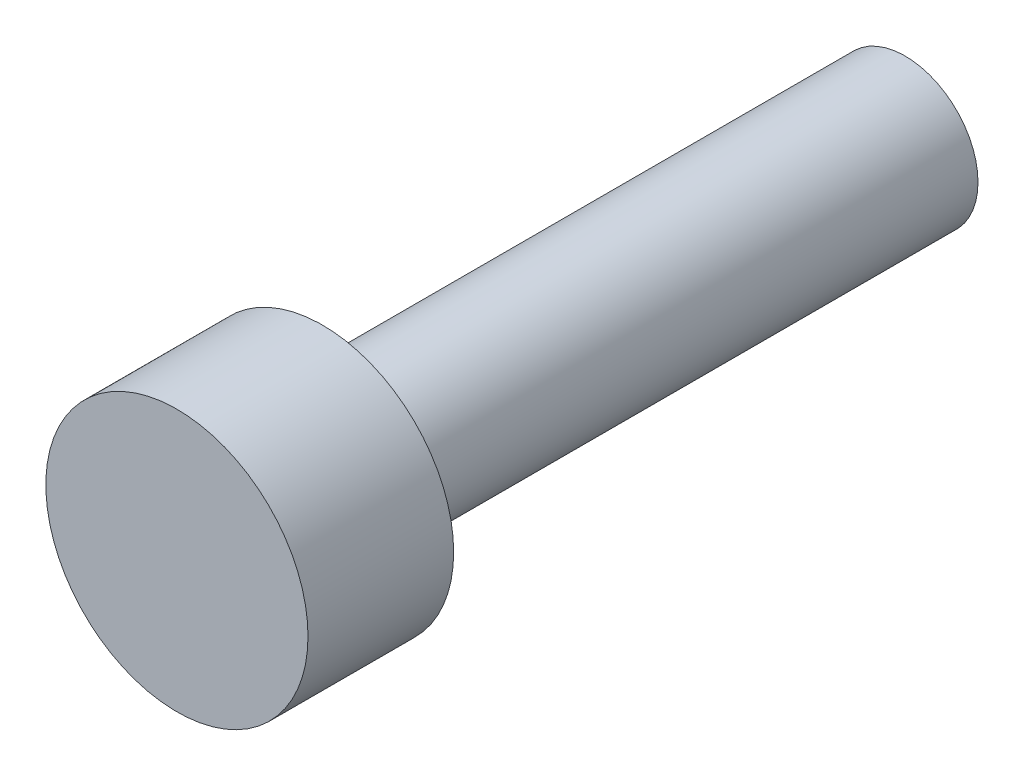
SolidWorks part; units mm, degrees
material "AISI 4340 Steel, normalized"
ref_plane "Front Plane" through (0, 0, 0) normal (0, 0, 1) x (1, 0, 0)
ref_plane "Top Plane" through (0, 0, 0) normal (0, 1, 0) x (1, 0, 0)
ref_plane "Right Plane" through (0, 0, 0) normal (1, 0, 0) x (0, 0, -1)
sketch "Sketch1" plane through (0, 0, 0) normal (0, 0, 1) x (1, 0, 0)
  circle A0 centre (0, 0) radius 2.25
extrude "ISO4762_M2p5_Head_Envelope" add sketch "Sketch1" along normal blind 2.5
sketch "Sketch2" plane through (0, 0, 0) normal (0, 0, 1) x (1, 0, 0)
  circle A0 centre (0, 0) radius 1.25
extrude "M2p5x0p45x10_Thread_Major_Envelope" add sketch "Sketch2" along normal blind 10 from offset 10
